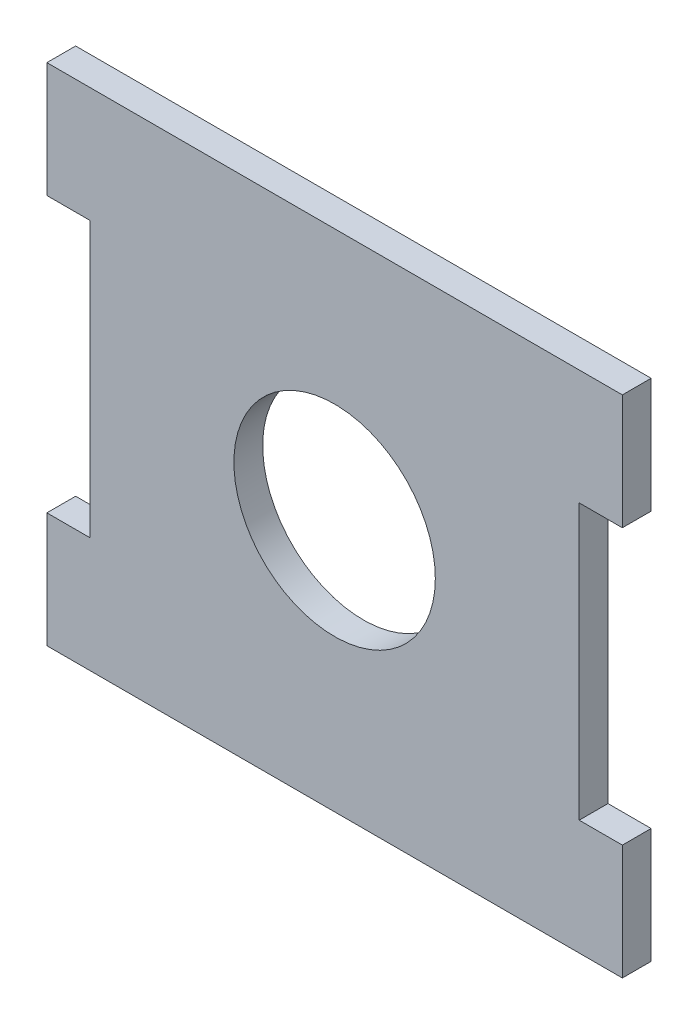
SolidWorks part; units mm, degrees
ref_plane "前视基准面" through (0, 0, 0) normal (0, 0, 1) x (1, 0, 0)
ref_plane "上视基准面" through (0, 0, 0) normal (0, 1, 0) x (1, 0, 0)
ref_plane "右视基准面" through (0, 0, 0) normal (1, 0, 0) x (0, 0, -1)
sketch "草图1" plane through (0, 0, 0) normal (0, 0, 1) x (1, 0, 0)
  line L0 (0, 0) -> (3, 0)
  line L1 (3, 0) -> (3, -8)
  line L2 (3, -8) -> (0, -8)
  line L3 (0, -8) -> (0, -27.1)
  line L4 (0, -27.1) -> (3, -27.1)
  line L5 (3, -27.1) -> (3, -35.1)
  line L6 (3, -35.1) -> (0, -35.1)
  line L7 (-17, 0) -> (-17, -8) construction
  line L8 (0, 0) -> (-34, 0)
  line L9 (-37, -35.1) -> (-34, -35.1)
  line L10 (-37, -27.1) -> (-37, -35.1)
  line L11 (-34, -27.1) -> (-37, -27.1)
  line L12 (-34, -8) -> (-34, -27.1)
  line L13 (-37, -8) -> (-34, -8)
  line L14 (-37, 0) -> (-37, -8)
  line L15 (-34, 0) -> (-37, 0)
  line L16 (0, -35.1) -> (-34, -35.1)
  line L17 (0, -8) -> (-34, -27.1) construction
  circle A0 centre (-17, -17.55) radius 7
extrude "凸台-拉伸1" add sketch "草图1" along normal blind 2
